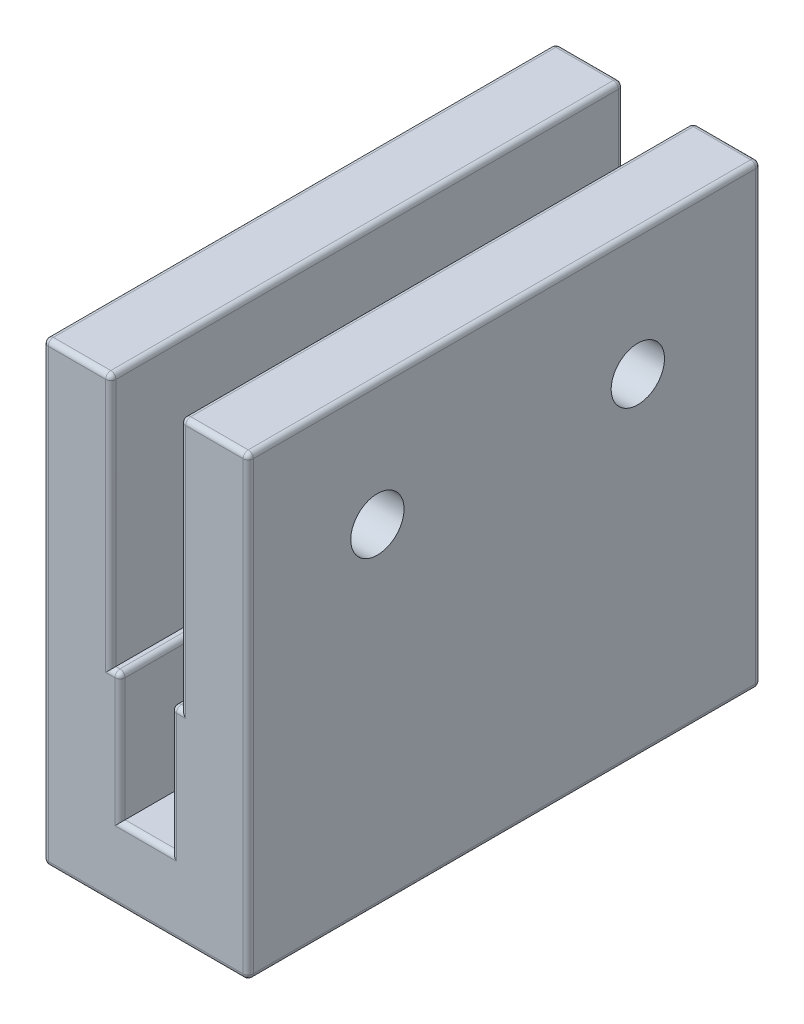
SolidWorks part; units mm, degrees
ref_plane "Front Plane" through (0, 0, 0) normal (0, 0, 1) x (1, 0, 0)
ref_plane "Top Plane" through (0, 0, 0) normal (0, 1, 0) x (1, 0, 0)
ref_plane "Right Plane" through (0, 0, 0) normal (1, 0, 0) x (0, 0, -1)
sketch "Sketch2" plane through (0, 0, 0) normal (0, 1, 0) x (1, 0, 0)
  line L1 (-10, 25) -> (10, 25)
  line L2 (-10, 25) -> (-10, -25)
  line L3 (-10, -25) -> (10, -25)
  line L4 (10, 25) -> (10, -25)
  line L5 (-10, 25) -> (10, -25) construction
  line L6 (-10, -25) -> (10, 25) construction
  point P1 (0, 0)
  dimension "D1" = 20
  dimension "D2" = 50
extrude "Boss-Extrude1" add sketch "Sketch2" along normal blind 44.5
sketch "Sketch3" plane through (0, 0, 25) normal (0, 0, 1) x (1, 0, 0)
  line L0 (-10, 44.5) -> (10, 44.5) construction
  line L1 (-3.4, 44.5) -> (3.4, 44.5)
  line L2 (-3.4, 44.5) -> (-3.4, 19.75)
  line L3 (-3.4, 19.75) -> (3.4, 19.75)
  line L4 (3.4, 44.5) -> (3.4, 19.75)
  line L7 (-2.5, 7.25) -> (2.5, 7.25)
  line L8 (-2.5, 7.25) -> (-2.5, 19.75)
  line L9 (-2.5, 19.75) -> (2.5, 19.75)
  line L10 (2.5, 7.25) -> (2.5, 19.75)
  point P8 (0, 19.75)
  point P12 (0, 19.75)
  dimension "D1" = 6.8
  dimension "D2" = 24.75
  dimension "D3" = 5
  dimension "D4" = 12.5
extrude "Cut-Extrude3" cut sketch "Sketch3" against normal through all contours L10 L9 L8 L7 | L2 L3 L4 L1
sketch "Sketch7" plane through (-10, 0, 0) normal (-1, 0, 0) x (0, 0, 1)
  line L0 (-25, 0) -> (25, 0) construction
  line L1 (-18.6, 3.48) -> (-14, 3.48)
  line L2 (-18.6, 3.48) -> (-18.6, 23.58)
  line L3 (-18.6, 23.58) -> (-14, 23.58)
  line L4 (-14, 3.48) -> (-14, 23.58)
  line L5 (-25, 44.5) -> (-25, 0) construction
  line L6 (0, 44.5) -> (0, 0) construction
  line L7 (-25, 44.5) -> (25, 44.5) construction
  line L8 (18.6, 23.58) -> (14, 23.58)
  line L9 (14, 3.48) -> (14, 23.58)
  line L10 (18.6, 3.48) -> (14, 3.48)
  line L11 (18.6, 3.48) -> (18.6, 23.58)
  dimension "D1" = 3.48
  dimension "D2" = 20.1
  dimension "D3" = 4.6
  dimension "D4" = 6.4
fillet "Fillet1" radius 0.5 32 edges at (-10, 0, 0) (10, 0, 0) (-10, 22.25, -25) (0, 0, -25) (10, 22.25, -25) (3.4, 32.125, -25) (2.95, 19.75, -25) (2.5, 13.5, -25) (0, 7.25, -25) (-2.5, 13.5, -25) (-2.95, 19.75, -25) (-3.4, 32.125, -25) (-2.5, 13.5, 25) (0, 7.25, 25) (2.5, 13.5, 25) (2.95, 19.75, 25) (3.4, 32.125, 25) (10, 22.25, 25) (0, 0, 25) (-10, 22.25, 25) (-3.4, 32.125, 25) (-2.95, 19.75, 25) (10, 44.5, 0) (6.7, 44.5, 25) (3.4, 44.5, 0) (6.7, 44.5, -25) (-6.7, 44.5, 25) (-10, 44.5, 0) (-6.7, 44.5, -25) (-3.4, 44.5, 0) (2.5, 19.75, 0) (-2.5, 19.75, 0)
extrude "Cut-Extrude4" cut sketch "Sketch7" against normal blind 3.25 contours L9 L8 L11 L10
sketch "Sketch8" plane through (-10, 0, 0) normal (-1, 0, 0) x (0, 0, 1)
  line L0 (-25, 0) -> (25, 0) construction
  line L1 (-25, 44.5) -> (-25, 0) construction
  circle A0 centre (-13, 32.41) radius 2.6
  circle A1 centre (12.4, 32.41) radius 2.6
  dimension "D2" = 5.2
  dimension "D1" = 32.41
  dimension "D3" = 12
  dimension "D4" = 25.4
extrude "Cut-Extrude5" cut sketch "Sketch8" against normal through all and the other way through all
